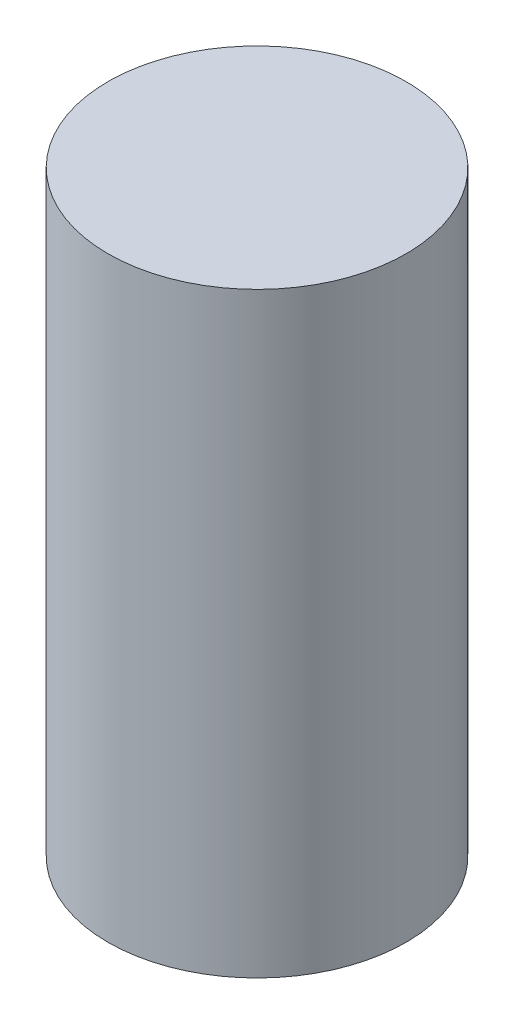
SolidWorks part; units mm, degrees
material "PP Kopolimer"
ref_plane "Front Plane" through (0, 0, 0) normal (0, 0, 1) x (1, 0, 0)
ref_plane "Top Plane" through (0, 0, 0) normal (0, 1, 0) x (1, 0, 0)
ref_plane "Right Plane" through (0, 0, 0) normal (1, 0, 0) x (0, 0, -1)
sketch "Szkic1" plane through (0, 0, 0) normal (0, 1, 0) x (1, 0, 0)
  circle A0 centre (0, 0) radius 0.5
extrude "Dodanie-wyciągnięcie1" add sketch "Szkic1" along normal blind 2
